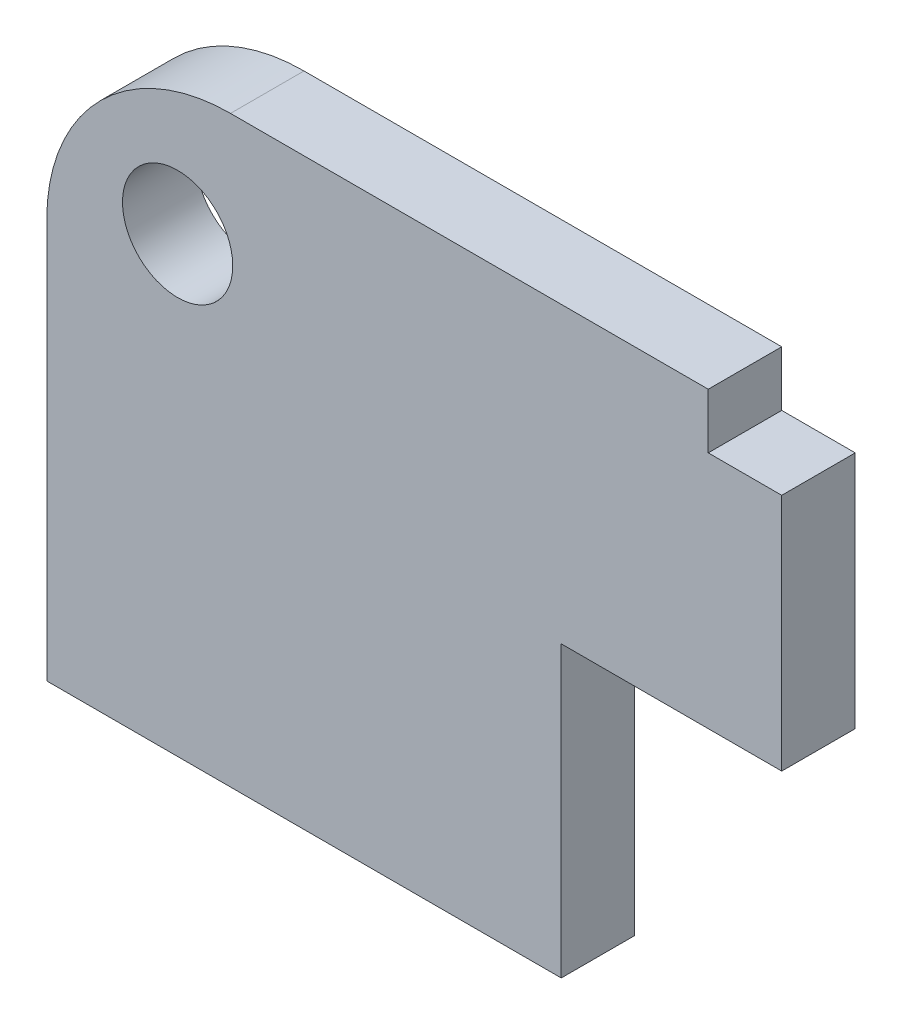
SolidWorks part; units mm, degrees
ref_plane "Front Plane" through (0, 0, 0) normal (0, 0, 1) x (1, 0, 0)
ref_plane "Top Plane" through (0, 0, 0) normal (0, 1, 0) x (1, 0, 0)
ref_plane "Right Plane" through (0, 0, 0) normal (1, 0, 0) x (0, 0, -1)
sketch "Sketch1" plane through (0, 0, 0) normal (0, 0, 1) x (1, 0, 0)
  line L0 (14, -8) -> (20, -8)
  line L7 (14, -15.8756) -> (0, -15.8756)
  line L8 (14, -15.8756) -> (14, -8)
  line L9 (20, -1.5) -> (20, -8)
  line L10 (5, 0) -> (18, 0)
  line L11 (18, -1.5) -> (18, 0)
  line L12 (20, -1.5) -> (18, -1.5)
  line L13 (0, -15.8756) -> (0, -5)
  arc A0 (0, -5) -> (5, 0) centre (5, -5) cw
  circle A1 centre (3.5607, -3.5607) radius 1.5
  point P2 (0, 0)
  dimension "D7" = 5
  dimension "D1" = 18
  dimension "D2" = 14
  dimension "D3" = 1.5
  dimension "D4" = 2
extrude "Boss-Extrude1" add sketch "Sketch1" along normal blind 2
